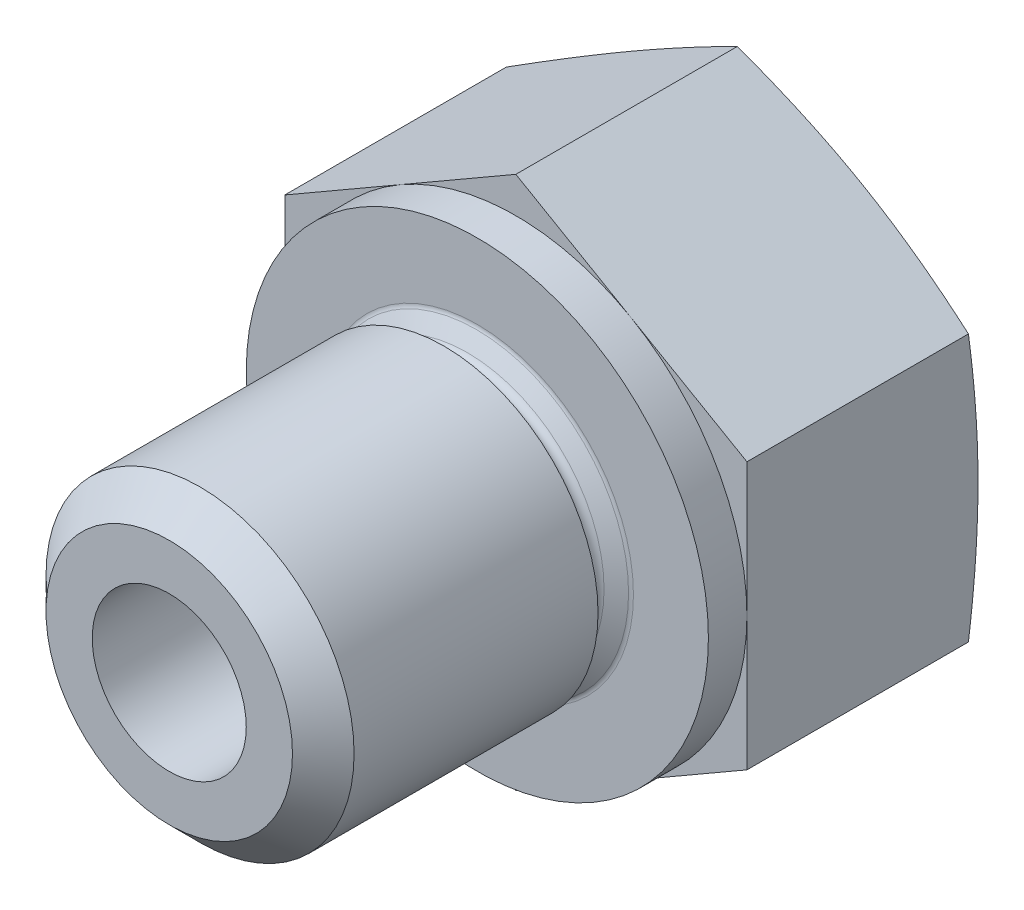
SolidWorks part; units mm, degrees
ref_plane "Přední rovina" through (0, 0, 0) normal (0, 0, 1) x (1, 0, 0)
ref_plane "Vrchní rovina" through (0, 0, 0) normal (0, 1, 0) x (1, 0, 0)
ref_plane "Pravá rovina" through (0, 0, 0) normal (1, 0, 0) x (0, 0, -1)
sketch "Skica1" plane through (0, 0, 0) normal (0, 0, 1) x (1, 0, 0)
  line L1 (6, 3.4641) -> (0, 6.9282)
  line L2 (0, 6.9282) -> (-6, 3.4641)
  line L3 (-6, 3.4641) -> (-6, -3.4641)
  line L4 (-6, -3.4641) -> (0, -6.9282)
  line L5 (0, -6.9282) -> (6, -3.4641)
  line L6 (6, -3.4641) -> (6, 3.4641)
  circle A0 centre (0, 0) radius 6 construction
  dimension "s" = 12
extrude "Vysunout1" add sketch "Skica1" along normal blind 6
sketch "Skica2" plane through (0, 0, 0) normal (0, 1, 0) x (1, 0, 0)
  line L0 (6, 0) -> (28.3923, 0)
  line L1 (28.3923, 0) -> (28.3923, -6)
  line L2 (28.3923, -6) -> (6, 0)
  line L3 (6, -6) -> (0, -6) construction
  line L4 (0, 0) -> (0, -6) construction
  dimension "D1" = 15
revolve "Odebrat otočením1" cut sketch "Skica2" angle 360 about L4
sketch "Skica3" plane through (0, 0, 6) normal (0, 0, 1) x (1, 0, 0)
  circle A0 centre (0, 0) radius 6
  dimension "D 1" = 12
extrude "Vysunout2" add sketch "Skica3" along normal blind 1
sketch "Skica4" plane through (0, 0, 7) normal (0, 0, 1) x (1, 0, 0)
  circle A0 centre (0, 0) radius 4
  dimension "Md" = 8
extrude "Vysunout3" add sketch "Skica4" along normal blind 8
cosmetic thread "Kosmetický závit1" parameters "D2"=6.8
chamfer "Zkosit1" distance 0.8 angle 45 1 edges at (4, 0, 15)
sketch "Skica6" plane through (0, 0, 0) normal (0, 1, 0) x (1, 0, 0)
  line L0 (0, -15) -> (0, 0) construction
  line L1 (-3.2, -15) -> (3.2, -15) construction
  line L2 (0, -11.4641) -> (2, -12)
  line L3 (2, -12) -> (2, -15)
  line L4 (2, -15) -> (0, -15)
  line L5 (0, -15) -> (0, -11.4641)
  dimension "d1" = 4
  dimension "D2" = 75
  dimension "h" = 3
revolve "Odebrat otočením2" cut sketch "Skica6" angle 360 about L0
fillet "Zaoblit1" radius 0.2 1 edges at (2, 0, 12)
sketch "Skica7" plane through (0, 0, 0) normal (0, 1, 0) x (1, 0, 0)
  line L0 (4, -7) -> (3.25, -7.433)
  line L1 (-6, -7) -> (6, -7) construction
  line L2 (3.25, -7.433) -> (4, -7.866)
  line L3 (4, -14.2) -> (4, -7) construction
  line L4 (4, -7.866) -> (4, -7)
  line L5 (3.25, -7.433) -> (4, -7.433) construction
  line L6 (0, 0) -> (0, -15) construction
  line L7 (-2, -15) -> (2, -15) construction
  dimension "D1" = 60
  dimension "d2" = 6.5
revolve "Odebrat otočením3" cut sketch "Skica7" angle 360 about L6
fillet "Zaoblit2" radius 0.2 2 edges at (-3.25, 0, 7.433) (-4, 0, 7)
equation "\"D1@Zaoblit1\" = 0.05*\"d1@Skica6\""
equation "\"D2@Kosmetický závit1\" = \"Md@Skica4\"*0.85"
